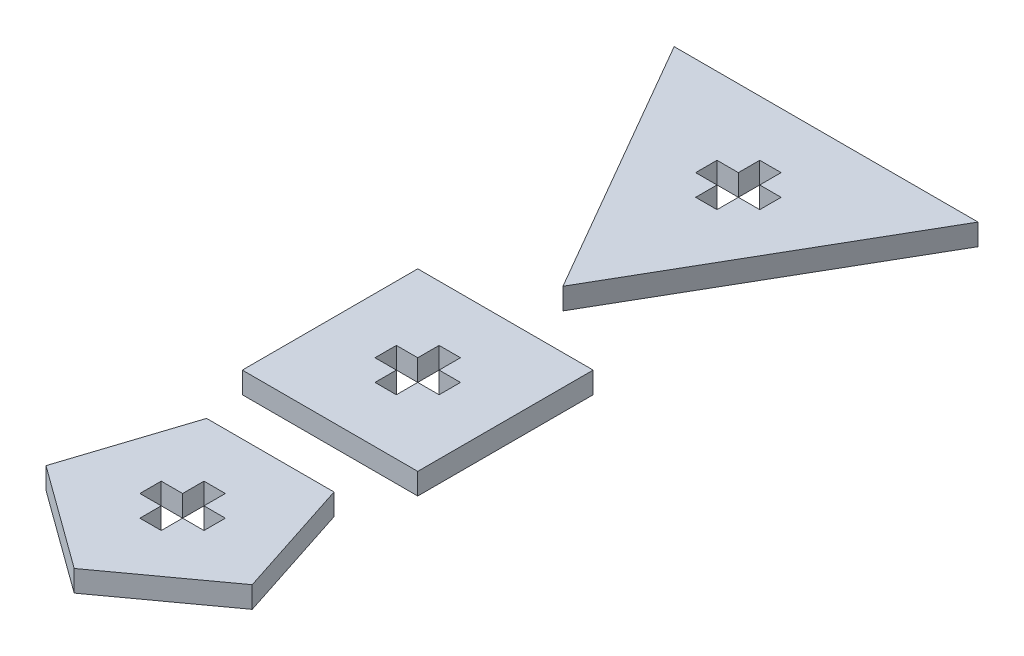
SolidWorks part; units mm, degrees
ref_plane "Front Plane" through (0, 0, 0) normal (0, 0, 1) x (1, 0, 0)
ref_plane "Top Plane" through (0, 0, 0) normal (0, 1, 0) x (1, 0, 0)
ref_plane "Right Plane" through (0, 0, 0) normal (1, 0, 0) x (0, 0, -1)
sketch "Sketch3" plane through (0, 0, 0) normal (0, 1, 0) x (1, 0, 0)
  line L0 (-14.7499, 42.5779) -> (-14.7499, -167.4037) construction
  line L1 (-101.2607, -33.6221) -> (115.7012, -33.6221) construction
  line L2 (-14.7499, 0.8889) -> (21.3539, 63.4225)
  line L3 (21.3539, 63.4225) -> (-50.8536, 63.4225)
  line L4 (-50.8536, 63.4225) -> (-14.7499, 0.8889)
  line L5 (-7.1299, -31.0821) -> (-7.1299, -33.6221)
  line L6 (-35.5944, -12.7775) -> (6.0946, -12.7775)
  line L7 (-35.5944, -12.7775) -> (-35.5944, -54.4666)
  line L8 (-35.5944, -54.4666) -> (6.0946, -54.4666)
  line L9 (-14.7499, -115.2673) -> (9.7543, -97.4639)
  line L10 (9.7543, -97.4639) -> (0.3946, -68.6575)
  line L11 (0.3946, -68.6575) -> (-29.8943, -68.6575)
  line L12 (-29.8943, -68.6575) -> (-39.2541, -97.4639)
  line L13 (-39.2541, -97.4639) -> (-14.7499, -115.2673)
  line L14 (-101.2607, -89.5021) -> (118.9707, -89.5021) construction
  line L15 (-101.2607, 42.5779) -> (117.3544, 42.5779) construction
  line L16 (-14.7499, 42.5779) -> (-14.7499, 86.087) construction
  line L17 (-14.7499, 50.1979) -> (-12.2099, 50.1979)
  line L18 (-12.2099, 50.1979) -> (-12.2099, 45.1179)
  line L19 (-12.2099, 45.1179) -> (-7.1299, 45.1179)
  line L20 (-7.1299, 45.1179) -> (-7.1299, 42.5779)
  line L21 (-7.1299, 42.5779) -> (-7.1299, 40.0379)
  line L22 (-7.1299, 40.0379) -> (-12.2099, 40.0379)
  line L23 (-12.2099, 40.0379) -> (-12.2099, 34.9579)
  line L24 (-12.2099, 34.9579) -> (-14.7499, 34.9579)
  line L25 (-14.7499, 34.9579) -> (-17.2899, 34.9579)
  line L26 (-17.2899, 34.9579) -> (-17.2899, 40.0379)
  line L27 (-17.2899, 40.0379) -> (-22.3699, 40.0379)
  line L28 (-22.3699, 40.0379) -> (-22.3699, 42.5779)
  line L29 (-22.3699, 42.5779) -> (-22.3699, 45.1179)
  line L30 (-22.3699, 45.1179) -> (-17.2899, 45.1179)
  line L31 (-17.2899, 45.1179) -> (-17.2899, 50.1979)
  line L32 (-17.2899, 50.1979) -> (-14.7499, 50.1979)
  line L33 (6.0946, -12.7775) -> (6.0946, -54.4666)
  line L34 (-35.5944, -12.7775) -> (6.0946, -54.4666) construction
  line L35 (-35.5944, -54.4666) -> (6.0946, -12.7775) construction
  line L36 (-17.2899, -36.1621) -> (-22.3699, -36.1621)
  line L37 (-14.7499, -26.0021) -> (-12.2099, -26.0021)
  line L38 (-12.2099, -41.2421) -> (-14.7499, -41.2421)
  line L39 (-17.2899, -31.0821) -> (-17.2899, -26.0021)
  line L40 (-7.1299, -33.6221) -> (-7.1299, -36.1621)
  line L41 (-22.3699, -36.1621) -> (-22.3699, -33.6221)
  line L42 (-12.2099, -26.0021) -> (-12.2099, -31.0821)
  line L43 (-14.7499, -41.2421) -> (-17.2899, -41.2421)
  line L44 (-17.2899, -26.0021) -> (-14.7499, -26.0021)
  line L45 (-7.1299, -36.1621) -> (-12.2099, -36.1621)
  line L46 (-22.3699, -33.6221) -> (-22.3699, -31.0821)
  line L47 (-12.2099, -31.0821) -> (-7.1299, -31.0821)
  line L48 (-17.2899, -41.2421) -> (-17.2899, -36.1621)
  line L49 (-22.3699, -92.0421) -> (-22.3699, -89.5021)
  line L50 (-12.2099, -81.8821) -> (-12.2099, -86.9621)
  line L51 (-17.2899, -81.8821) -> (-14.7499, -81.8821)
  line L52 (-14.7499, -97.1221) -> (-17.2899, -97.1221)
  line L53 (-7.1299, -92.0421) -> (-12.2099, -92.0421)
  line L54 (-22.3699, -89.5021) -> (-22.3699, -86.9621)
  line L55 (-12.2099, -86.9621) -> (-7.1299, -86.9621)
  line L56 (-17.2899, -97.1221) -> (-17.2899, -92.0421)
  line L57 (-12.2099, -92.0421) -> (-12.2099, -97.1221)
  line L58 (-22.3699, -86.9621) -> (-17.2899, -86.9621)
  line L59 (-7.1299, -86.9621) -> (-7.1299, -89.5021)
  line L60 (-17.2899, -92.0421) -> (-22.3699, -92.0421)
  line L61 (-14.7499, -81.8821) -> (-12.2099, -81.8821)
  line L62 (-12.2099, -97.1221) -> (-14.7499, -97.1221)
  line L63 (-17.2899, -86.9621) -> (-17.2899, -81.8821)
  line L64 (-7.1299, -89.5021) -> (-7.1299, -92.0421)
  line L65 (-12.2099, -36.1621) -> (-12.2099, -41.2421)
  line L66 (-22.3699, -31.0821) -> (-17.2899, -31.0821)
  circle A0 centre (-14.7499, 42.5779) radius 20.8445 construction
  circle A2 centre (-14.7499, -89.5021) radius 20.8445 construction
  point P2 (-14.7499, -33.6221)
  point P3 (-14.7499, 42.5779)
  point P4 (-14.7499, -89.5021)
  point P5 (-14.7499, -33.6221)
  point P15 (-14.7499, -33.6221)
  point P37 (-14.7499, 42.5779)
  point P43 (-14.7499, 42.5779)
  point P49 (-14.7499, 42.5779)
  point P50 (-14.7499, -33.6221)
  point P55 (-14.7499, 42.5779)
  point P59 (-14.7499, -33.6221)
  point P64 (-14.7499, -33.6221)
  point P68 (-14.7499, -33.6221)
  point P70 (-14.7499, -89.5021)
  point P76 (-14.7499, -89.5021)
  point P81 (-14.7499, -89.5021)
  point P86 (-14.7499, -89.5021)
  point P90 (-14.7499, -89.5021)
  dimension "D3" = 41.689
  dimension "D4" = 76.2
  dimension "D5" = 41.689
  dimension "D2" = 55.88
  dimension "D6" = 2.54
  dimension "D7" = 5.08
  dimension "D8" = 2.54
  dimension "D9" = 5.08
  dimension "D11" = 41.689
  dimension "D12" = 41.689
  dimension "D13" = 2.54
  dimension "D14" = 2.54
  dimension "D15" = 5.08
  dimension "D16" = 5.08
  dimension "D17" = 5.08
  dimension "D10" = 4
extrude "Boss-Extrude1" add sketch "Sketch3" along normal blind 5.08
